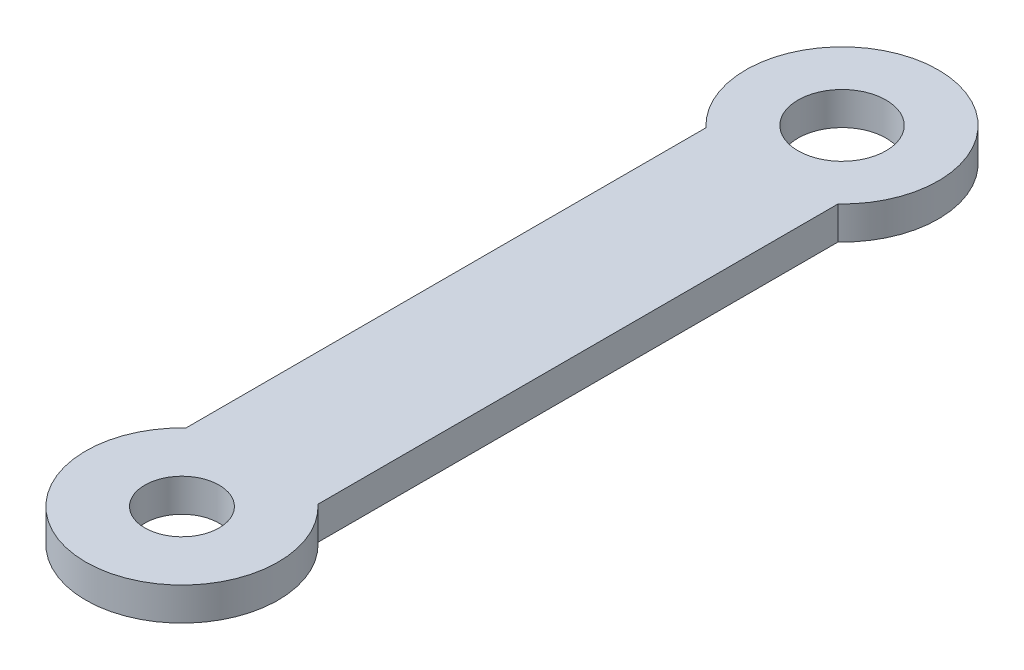
SolidWorks part; units mm, degrees
ref_plane "Alzado" through (0, 0, 0) normal (0, 0, 1) x (1, 0, 0)
ref_plane "Planta" through (0, 0, 0) normal (0, 1, 0) x (1, 0, 0)
ref_plane "Vista lateral" through (0, 0, 0) normal (1, 0, 0) x (0, 0, -1)
sketch "Croquis1" plane through (0, 0, 0) normal (0, 1, 0) x (1, 0, 0)
  line L0 (0, 0) -> (0, 60) construction
  line L2 (-6, 30) -> (-6, 53.6311)
  line L3 (-6, 30) -> (-6, 6.3689)
  line L4 (6, 30) -> (6, 53.6311)
  line L5 (6, 30) -> (6, 6.3689)
  circle A0 centre (0, 60) radius 4
  arc A1 (6, 53.6311) -> (-6, 53.6311) centre (0, 60) ccw
  arc A2 (-6, 6.3689) -> (6, 6.3689) centre (0, 0) ccw
  circle A3 centre (0, 0) radius 3.375
  dimension "D2" = 8
  dimension "D3" = 17.5
  dimension "D5" = 17.5
  dimension "D4" = 6.75
  dimension "D1" = 60
extrude "Saliente-Extruir1" add sketch "Croquis1" along normal blind 3
